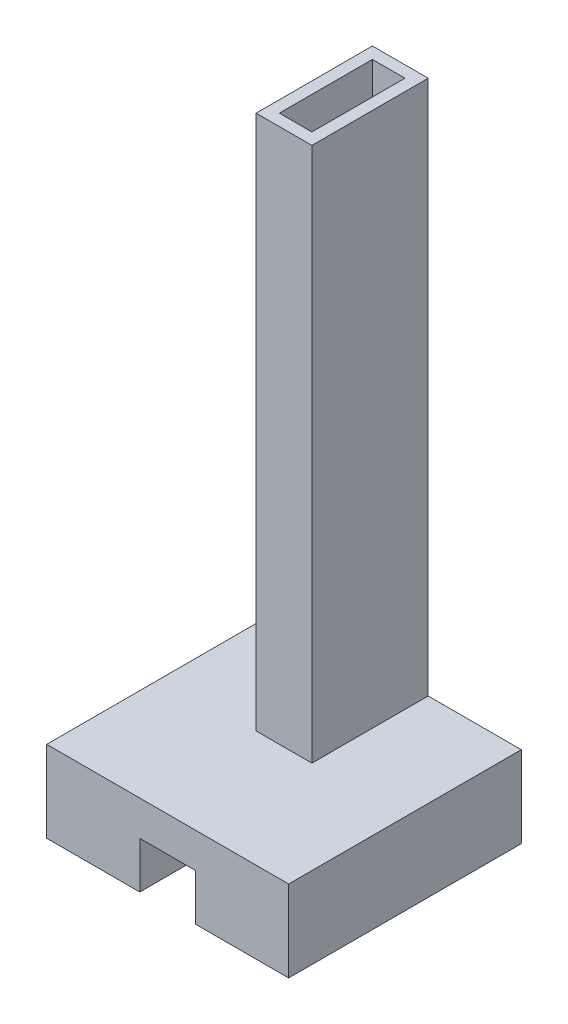
SolidWorks part; units mm, degrees
ref_plane "Ebene vorne" through (0, 0, 0) normal (0, 0, 1) x (1, 0, 0)
ref_plane "Ebene oben" through (0, 0, 0) normal (0, 1, 0) x (1, 0, 0)
ref_plane "Ebene rechts" through (0, 0, 0) normal (1, 0, 0) x (0, 0, -1)
sketch "Skizze1" plane through (0, 0, 0) normal (0, 0, 1) x (1, 0, 0)
  line L1 (0, 0) -> (1040, 0)
  line L2 (0, 0) -> (0, 350)
  line L3 (0, 350) -> (1040, 350)
  line L4 (1040, 0) -> (1040, 350)
  dimension "D1" = 1040
  dimension "D2" = 350
extrude "Aufsatz-Linear austragen1" add sketch "Skizze1" along normal blind 1000
sketch "Skizze2" plane through (0, 0, 1000) normal (0, 0, 1) x (1, 0, 0)
  line L0 (0, 0) -> (1040, 0) construction
  line L1 (400, 0) -> (640, 0)
  line L2 (400, 0) -> (400, 200)
  line L3 (400, 200) -> (640, 200)
  line L4 (640, 0) -> (640, 200)
  line L5 (0, 350) -> (0, 0) construction
  line L6 (1040, 0) -> (1040, 350) construction
  dimension "D1" = 400
  dimension "D2" = 400
  dimension "D3" = 200
extrude "Schnitt-Linear austragen1" cut sketch "Skizze2" against normal through all
sketch "Skizze3" plane through (0, 350, 0) normal (0, 1, 0) x (1, 0, 0)
  line L0 (1040, 0) -> (0, 0) construction
  line L1 (400, 0) -> (640, 0)
  line L2 (400, 0) -> (400, -500)
  line L3 (400, -500) -> (640, -500)
  line L4 (640, 0) -> (640, -500)
  line L5 (1040, -1000) -> (1040, 0) construction
  line L6 (0, -1000) -> (0, 0) construction
  dimension "D1" = 500
  dimension "D2" = 400
  dimension "D3" = 400
extrude "Aufsatz-Linear austragen2" add sketch "Skizze3" along normal blind 2300
sketch "Skizze4" plane through (0, 2650, 0) normal (0, 1, 0) x (1, 0, 0)
  line L0 (640, 0) -> (400, 0) construction
  line L1 (450, -50) -> (590, -50)
  line L2 (450, -50) -> (450, -450)
  line L3 (450, -450) -> (590, -450)
  line L4 (590, -50) -> (590, -450)
  line L5 (400, -500) -> (640, -500) construction
  line L6 (640, -500) -> (640, 0) construction
  line L7 (400, 0) -> (400, -500) construction
  dimension "D1" = 50
  dimension "D2" = 50
  dimension "D3" = 50
  dimension "D4" = 50
extrude "Schnitt-Linear austragen2" cut sketch "Skizze4" against normal through all
